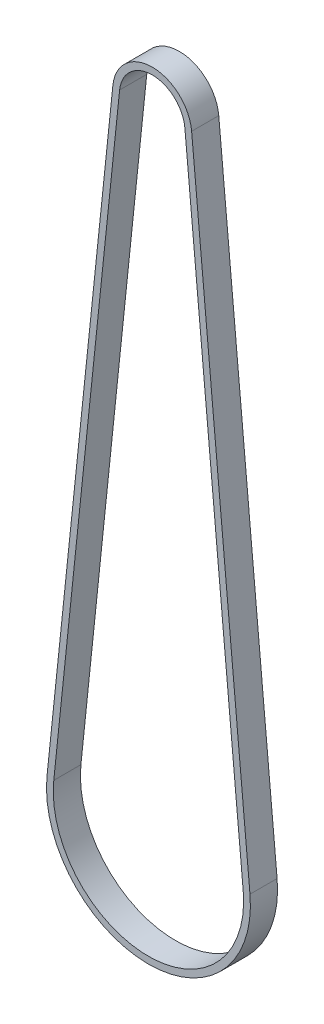
SolidWorks part; units mm, degrees
ref_plane "前视基准面" through (0, 0, 0) normal (0, 0, 1) x (1, 0, 0)
ref_plane "上视基准面" through (0, 0, 0) normal (0, 1, 0) x (1, 0, 0)
ref_plane "右视基准面" through (0, 0, 0) normal (1, 0, 0) x (0, 0, -1)
other "Configuration Table"
sketch "草图2" plane through (0, 0, 0) normal (0, 0, 1) x (1, 0, 0)
  line L0 (0, 0) -> (1, 0) construction
  line L1 (0, 0) -> (0, 1) construction
  line L2 (7.2193, 0.6669) -> (20.1215, -139.0014)
  line L3 (-21.7755, -138.7519) -> (-7.2108, 0.7528)
  arc A0 (-7.2108, 0.7528) -> (7.2193, 0.6669) centre (0, 0) cw
  arc A1 (20.1215, -139.0014) -> (-21.7755, -138.7519) centre (-0.8393, -140.9377) cw
extrude "拉伸-薄壁1" add sketch "草图2" along normal blind 6 thin thin type one direction wall 1.5
